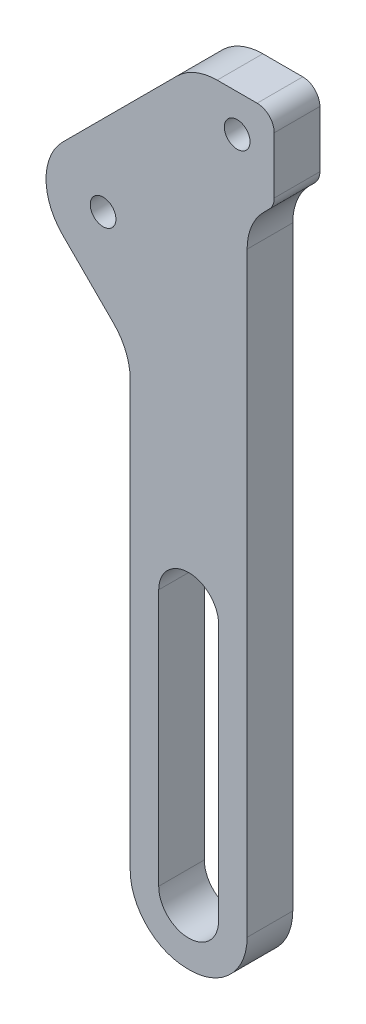
SolidWorks part; units mm, degrees
ref_plane "Front Plane" through (0, 0, 0) normal (0, 0, 1) x (1, 0, 0)
ref_plane "Top Plane" through (0, 0, 0) normal (0, 1, 0) x (1, 0, 0)
ref_plane "Right Plane" through (0, 0, 0) normal (1, 0, 0) x (0, 0, -1)
sketch "Sketch1" plane through (0, 0, 0) normal (0, 0, 1) x (1, 0, 0)
  line L0 (15, -52.5) -> (15, -97.5) construction
  line L1 (-10, 30) -> (30, 30)
  line L2 (-10, 30) -> (-10, -107.5)
  line L3 (-10, -107.5) -> (30, -107.5)
  line L4 (30, 30) -> (30, -107.5)
  line L5 (20.25, -52.5) -> (20.25, -97.5)
  line L6 (9.75, -52.5) -> (9.75, -97.5)
  arc A0 (20.25, -52.5) -> (9.75, -52.5) centre (15, -52.5) ccw
  arc A1 (9.75, -97.5) -> (20.25, -97.5) centre (15, -97.5) ccw
  point P4 (15, -75)
  dimension "D1" = 30
  dimension "D2" = 10
  dimension "D3" = 30
  dimension "D4" = 10
  dimension "D5" = 10.5
  dimension "D6" = 45
  dimension "D7" = 97.5
  dimension "D8" = 15
extrude "Boss-Extrude1" add sketch "Sketch1" against normal blind 8
hole_wizard "CBORE for M4 SHCS1" positions "Sketch2" profile "Sketch3" counterbore size "M4" standard "ANSI Metric" end condition through all
sketch "Sketch2" plane through (0, 0, -8) normal (0, 0, 1) x (1, 0, 0)
  point P0 (0, 0)
  point P7 (23.51, 23.51)
  dimension "D1" = 23.51
  dimension "D2" = 23.51
sketch "Sketch3" plane through (0, 0, -8) normal (1, 0, 0) x (0, 1, 0)
  line L0 (0, 0) -> (0, 8)
  line L1 (0, 8) -> (2.25, 8)
  line L3 (2.25, 8) -> (2.25, 4)
  line L4 (2.25, 4) -> (4, 4)
  line L5 (4, 4) -> (4, 0)
  line L7 (4, 0) -> (0, 0)
  line L11 (0, -6.35) -> (0, 107.95) construction
  dimension "Thru Hole Dia." = 4.5
  dimension "Thru Hole Depth" = 8
  dimension "C'Bore Dia." = 8
  dimension "C'Bore Depth" = 4
sketch "Sketch6" plane through (0, 0, 0) normal (0, 0, 1) x (1, 0, 0)
  line L0 (4.75, -107.5) -> (4.75, -18.8921)
  line L1 (9.75, -52.5) -> (9.75, -97.5) construction
  line L2 (25.25, -107.5) -> (25.25, 11.1079)
  line L3 (20.25, -97.5) -> (20.25, -52.5) construction
  line L4 (-10, 30) -> (-10, -107.5)
  line L5 (-10, -107.5) -> (30, -107.5)
  line L6 (30, -107.5) -> (30, 30)
  line L7 (30, 30) -> (-10, 30)
  line L8 (-10, 30) -> (-10, -107.5)
  line L9 (-10, -107.5) -> (30, -107.5)
  line L10 (30, -107.5) -> (30, 30)
  line L11 (30, 30) -> (-10, 30)
  line L12 (-7.0711, -7.0711) -> (4.75, -18.8921)
  line L13 (25.25, 11.1079) -> (30, 15.8579)
  line L14 (-7.0711, 7.0711) -> (16.4389, 30.5811)
  circle A0 centre (0, 0) radius 10
  circle A1 centre (23.51, 23.51) radius 10
  line M12 (-10, 30) -> (-10, -107.5)
  line M13 (-10, -107.5) -> (30, -107.5)
  line M14 (30, -107.5) -> (30, 30)
  dimension "D2" = 5
  dimension "D3" = 5
  dimension "D4" = 135
  dimension "D5" = 135
  dimension "D1" = 0
extrude "Cut-Extrude1" cut sketch "Sketch6" against normal through all contours A0 L8 L0 L12 M13 | A0 L14 L11 M12 | L13 L2 M13 M14
fillet "Fillet1" radius 10 5 edges at (15.8579, 30, -4) (25.25, 11.1079, -4) (4.75, -18.8921, -4) (25.25, -107.5, -4) (4.75, -107.5, -4)
fillet "Fillet2" radius 3 2 edges at (30, 15.8579, -4) (30, 30, -4)
